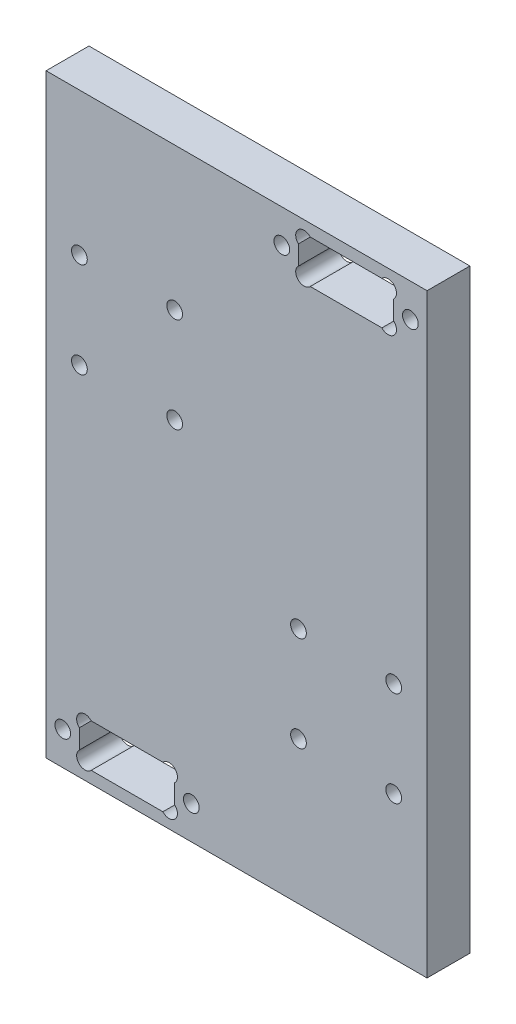
SolidWorks part; units mm, degrees
ref_plane "Plan de face" through (0, 0, 0) normal (0, 0, 1) x (1, 0, 0)
ref_plane "Plan de dessus" through (0, 0, 0) normal (0, 1, 0) x (1, 0, 0)
ref_plane "Plan de droite" through (0, 0, 0) normal (1, 0, 0) x (0, 0, -1)
sketch "Esquisse1" plane through (0, 0, 0) normal (0, 0, 1) x (1, 0, 0)
  line L1 (0, 0) -> (80, 0)
  line L2 (0, 0) -> (0, 125)
  line L3 (0, 125) -> (80, 125)
  line L4 (80, 0) -> (80, 125)
  dimension "D1" = 125
  dimension "D2" = 80
extrude "Boss.-Extru.1" add sketch "Esquisse1" along normal blind 9
sketch "Esquisse2" plane through (0, 0, 9) normal (0, 0, 1) x (1, 0, 0)
  line L0 (0, 0) -> (80, 0) construction
  line L1 (7, 11.5) -> (27, 11.5)
  line L2 (7, 11.5) -> (7, 2.5)
  line L3 (7, 2.5) -> (27, 2.5)
  line L4 (27, 11.5) -> (27, 2.5)
  line L5 (0, 125) -> (0, 0) construction
  line L6 (80, 125) -> (0, 125) construction
  line L7 (53, 122.5) -> (73, 122.5)
  line L8 (53, 122.5) -> (53, 113.5)
  line L9 (53, 113.5) -> (73, 113.5)
  line L10 (73, 122.5) -> (73, 113.5)
  line L11 (80, 0) -> (80, 125) construction
  dimension "D1" = 9
  dimension "D2" = 2.5
  dimension "D3" = 7
  dimension "D4" = 20
  dimension "D5" = 2.5
  dimension "D6" = 7
extrude "Enlèv. mat.-Extru.1" cut sketch "Esquisse2" against normal up to vertex (9 mm away)
sketch "Esquisse3" plane through (0, 0, 9) normal (0, 0, 1) x (1, 0, 0)
  line L0 (17, 11.5) -> (17, 2.5) construction
  line L1 (27, 11.5) -> (7, 11.5) construction
  line L2 (7, 2.5) -> (27, 2.5) construction
  line L3 (7, 7) -> (27, 7) construction
  line L4 (7, 11.5) -> (7, 2.5) construction
  line L5 (27, 2.5) -> (27, 11.5) construction
  line L6 (7, 9.0251) -> (9.4749, 11.5)
  line L7 (8.2374, 10.2626) -> (7, 11.5) construction
  line L8 (7, 11.5) -> (6.9293, 11.5707) construction
  line L9 (27, 11.5) -> (27.0707, 11.5707) construction
  line L10 (25.7626, 10.2626) -> (27, 11.5) construction
  line L11 (27, 9.0251) -> (24.5251, 11.5)
  line L12 (25.7626, 3.7374) -> (27, 2.5) construction
  line L13 (27, 2.5) -> (27.0707, 2.4293) construction
  line L14 (7, 2.5) -> (6.9293, 2.4293) construction
  line L15 (8.2374, 3.7374) -> (7, 2.5) construction
  line L16 (27, 4.9749) -> (24.5251, 2.5)
  line L17 (7, 4.9749) -> (9.4749, 2.5)
  line L18 (80, 62.5) -> (0, 62.5) construction
  line L19 (80, 0) -> (80, 125) construction
  line L20 (0, 125) -> (0, 0) construction
  line L21 (8.2374, 121.2626) -> (7, 122.5) construction
  line L22 (7, 122.5) -> (6.9293, 122.5707) construction
  line L23 (27, 122.5) -> (27.0707, 122.5707) construction
  line L24 (25.7626, 121.2626) -> (27, 122.5) construction
  line L25 (25.7626, 114.7374) -> (27, 113.5) construction
  line L26 (27, 113.5) -> (27.0707, 113.4293) construction
  line L27 (7, 113.5) -> (6.9293, 113.4293) construction
  line L28 (8.2374, 114.7374) -> (7, 113.5) construction
  line L29 (7, 118) -> (27, 118) construction
  line L30 (17, 113.5) -> (17, 122.5) construction
  line L31 (7, 120.0251) -> (9.4749, 122.5) construction
  line L32 (27, 120.0251) -> (24.5251, 122.5) construction
  line L33 (27, 115.9749) -> (24.5251, 113.5) construction
  line L34 (7, 115.9749) -> (9.4749, 113.5) construction
  line L35 (40, 62.5) -> (40, 125) construction
  line L36 (80, 125) -> (0, 125) construction
  line L37 (63, 113.5) -> (63, 122.5) construction
  line L38 (73, 118) -> (53, 118) construction
  line L39 (71.7626, 114.7374) -> (73, 113.5) construction
  line L40 (73, 113.5) -> (73.0707, 113.4293) construction
  line L41 (53, 113.5) -> (52.9293, 113.4293) construction
  line L42 (54.2374, 114.7374) -> (53, 113.5) construction
  line L43 (54.2374, 121.2626) -> (53, 122.5) construction
  line L44 (53, 122.5) -> (52.9293, 122.5707) construction
  line L45 (73, 122.5) -> (73.0707, 122.5707) construction
  line L46 (71.7626, 121.2626) -> (73, 122.5) construction
  line L47 (73, 115.9749) -> (70.5251, 113.5)
  line L48 (53, 115.9749) -> (55.4749, 113.5)
  line L49 (53, 120.0251) -> (55.4749, 122.5)
  line L50 (73, 120.0251) -> (70.5251, 122.5)
  line L51 (7, 7) -> (0, 7) construction
  arc A0 (7, 9.0251) -> (9.4749, 11.5) centre (8.1686, 10.3314) cw
  arc A1 (27, 9.0251) -> (24.5251, 11.5) centre (25.8314, 10.3314) ccw
  arc A2 (27, 4.9749) -> (24.5251, 2.5) centre (25.8314, 3.6686) cw
  arc A3 (7, 4.9749) -> (9.4749, 2.5) centre (8.1686, 3.6686) ccw
  arc A4 (7, 120.0251) -> (9.4749, 122.5) centre (8.1686, 121.3314) cw construction
  arc A5 (27, 120.0251) -> (24.5251, 122.5) centre (25.8314, 121.3314) ccw construction
  arc A6 (27, 115.9749) -> (24.5251, 113.5) centre (25.8314, 114.6686) cw construction
  arc A7 (7, 115.9749) -> (9.4749, 113.5) centre (8.1686, 114.6686) ccw construction
  arc A8 (73, 115.9749) -> (70.5251, 113.5) centre (71.8314, 114.6686) cw
  arc A9 (53, 115.9749) -> (55.4749, 113.5) centre (54.1686, 114.6686) ccw
  arc A10 (53, 120.0251) -> (55.4749, 122.5) centre (54.1686, 121.3314) cw
  arc A11 (73, 120.0251) -> (70.5251, 122.5) centre (71.8314, 121.3314) ccw
  circle A12 centre (3.5, 7) radius 1.65
  circle A13 centre (30.5, 7) radius 1.65
  circle A14 centre (30.5, 118) radius 1.65 construction
  circle A15 centre (3.5, 118) radius 1.65 construction
  circle A16 centre (49.5, 118) radius 1.65
  circle A17 centre (76.5, 118) radius 1.65
  dimension "D1" = 3.5
  dimension "D3" = 3.3
  dimension "D2" = 0.1
extrude "Enlèv. mat.-Extru.2" cut sketch "Esquisse3" against normal through all both and the other way through all
sketch "Esquisse4" plane through (0, 0, 9) normal (0, 0, 1) x (1, 0, 0)
  line L0 (17, 11.5) -> (17, 125) construction
  line L1 (24.5251, 11.5) -> (9.4749, 11.5) construction
  line L2 (80, 125) -> (0, 125) construction
  line L3 (40, 125) -> (40, 0) construction
  line L4 (0, 0) -> (80, 0) construction
  line L5 (17, 85) -> (0, 85) construction
  line L6 (0, 125) -> (0, 0) construction
  line L7 (40, 62.5) -> (0, 62.5) construction
  line L8 (17, 40) -> (0, 40) construction
  line L9 (63, 40) -> (80, 40) construction
  circle A0 centre (7, 95) radius 1.65
  circle A1 centre (27, 95) radius 1.65
  circle A2 centre (27, 75) radius 1.65
  circle A3 centre (7, 75) radius 1.65
  circle A4 centre (7, 50) radius 1.65 construction
  circle A5 centre (27, 50) radius 1.65 construction
  circle A6 centre (27, 30) radius 1.65 construction
  circle A7 centre (7, 30) radius 1.65 construction
  circle A8 centre (73, 30) radius 1.65
  circle A9 centre (53, 30) radius 1.65
  circle A10 centre (53, 50) radius 1.65
  circle A11 centre (73, 50) radius 1.65
  dimension "D2" = 20
  dimension "D3" = 20
  dimension "D4" = 3.3
  dimension "D1" = 40
extrude "Enlèv. mat.-Extru.3" cut sketch "Esquisse4" against normal up to vertex (9 mm away)
